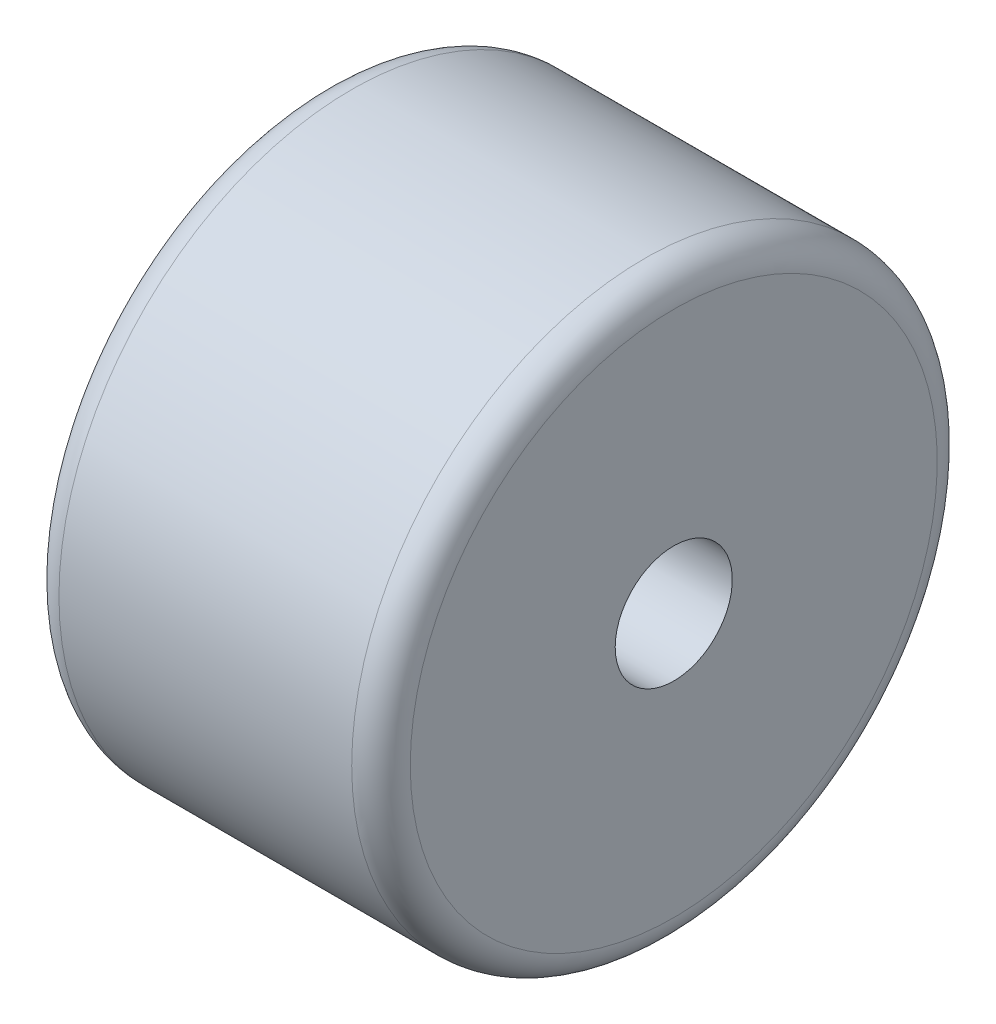
SolidWorks part; units mm, degrees
ref_plane "Plan de face" through (0, 0, 0) normal (0, 0, 1) x (1, 0, 0)
ref_plane "Plan de dessus" through (0, 0, 0) normal (0, 1, 0) x (1, 0, 0)
ref_plane "Plan de droite" through (0, 0, 0) normal (1, 0, 0) x (0, 0, -1)
sketch "Esquisse1" plane through (0, 0, 0) normal (0, 0, 1) x (1, 0, 0)
  line L0 (0, 0) -> (12, 0)
  line L1 (12, 0) -> (12, 9)
  line L2 (11, 10) -> (1, 10)
  line L3 (0, 9) -> (0, 0)
  line L4 (0, 2) -> (12, 2)
  arc A0 (12, 9) -> (11, 10) centre (11, 9) ccw
  arc A1 (1, 10) -> (0, 9) centre (1, 9) ccw
  point P8 (12, 10)
  point P11 (0, 10)
  dimension "D3" = 1
  dimension "D4" = 1
  dimension "D1" = 10
  dimension "D2" = 12
  dimension "D5" = 2
revolve "Révolution1" add sketch "Esquisse1" angle 360 about L0
